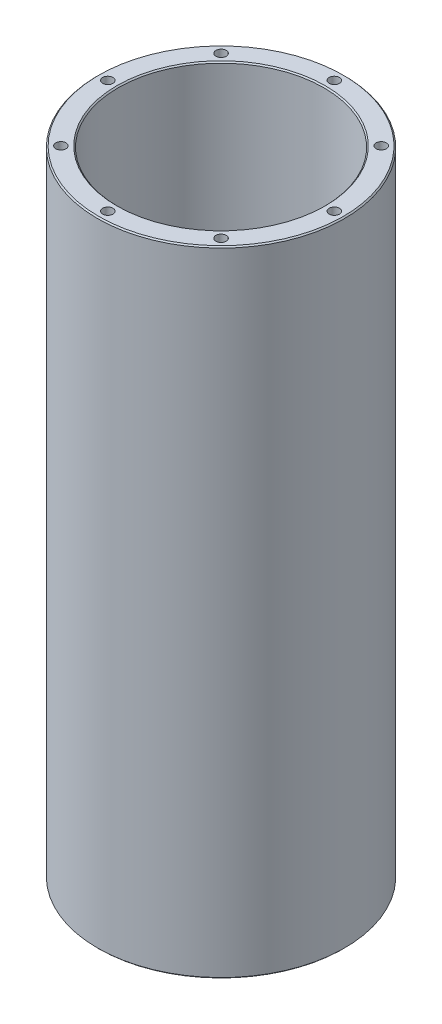
SolidWorks part; units mm, degrees
material "1.4305 (X8CrNiS18-9)"
ref_plane "Front Plane" through (0, 0, 0) normal (0, 0, 1) x (1, 0, 0)
ref_plane "Top Plane" through (0, 0, 0) normal (0, 1, 0) x (1, 0, 0)
ref_plane "Right Plane" through (0, 0, 0) normal (1, 0, 0) x (0, 0, -1)
sketch "Sketch1" plane through (0, 0, 0) normal (0, 1, 0) x (1, 0, 0)
  circle A0 centre (0, 0) radius 60 construction
  circle A1 centre (0, 0) radius 60
  circle A2 centre (0, 0) radius 50
  dimension "D1" = 10
extrude "Boss-Extrude1" add sketch "Sketch1" along normal up to vertex (154 mm away) and the other way up to vertex (154 mm away)
sketch "Sketch4" plane through (0, 154, 0) normal (0, 1, 0) x (1, 0, 0)
  line L0 (0, 60) -> (0, 50) construction
  line L1 (0, 0) -> (0, 55) construction
  line L2 (0, 0) -> (38.8909, 38.8909) construction
  circle A0 centre (0, 0) radius 60 construction
  circle A1 centre (0, 0) radius 50 construction
  point P11 (0, 55)
  point P18 (38.8909, 38.8909)
  point P19 (55, 0)
  point P20 (38.8909, -38.8909)
  point P21 (0, -55)
  point P22 (-38.8909, -38.8909)
  point P23 (-55, 0)
  point P24 (-38.8909, 38.8909)
  dimension "D2" = 45
  dimension "D1" = 8
hole_wizard "Tap Drill for M6 Tap1" positions "Sketch4" profile "Sketch3" hole size "M6" standard "DIN"
sketch "Sketch3" plane through (-38.8909, 154, -38.8909) normal (1, 0, 0) x (0, 0, 1)
  line L0 (0, 0) -> (0, 16.5022)
  line L1 (0, 16.5022) -> (2.5, 15)
  line L2 (2.5, 15) -> (2.5, 0)
  line L5 (2.5, 0) -> (0, 0)
  line L10 (0, 16.5022) -> (-2.5, 15) construction
  line L11 (0, -6.35) -> (0, 107.95) construction
  dimension "Hole Dia." = 5
  dimension "Hole Depth" = 15
  dimension "Drill Angle" = 118
mirror "Mirror1" about plane through (0, 0, 0) normal (0, 1, 0) of "Tap Drill for M6 Tap1"
chamfer "Chamfer1" distance 0.6 angle 45 4 edges at (0, -154, 50) (0, -154, 60) (0, 154, 50) (0, 154, 60)
